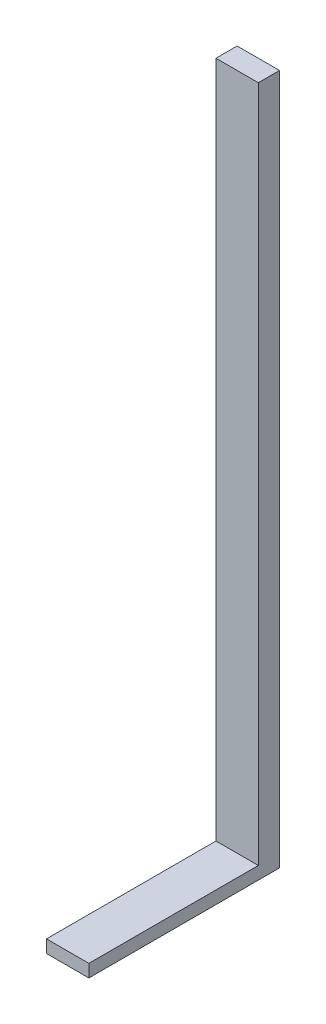
SolidWorks part; units mm, degrees
ref_plane "Front Plane" through (0, 0, 0) normal (0, 0, 1) x (1, 0, 0)
ref_plane "Top Plane" through (0, 0, 0) normal (0, 1, 0) x (1, 0, 0)
ref_plane "Right Plane" through (0, 0, 0) normal (1, 0, 0) x (0, 0, -1)
sketch "Sketch1" plane through (0, 0, 0) normal (1, 0, 0) x (0, 0, -1)
  line L0 (0, 0) -> (-45, 0)
  line L1 (-45, 0) -> (-45, 3)
  line L2 (-45, 3) -> (-5, 3)
  line L3 (-5, 3) -> (-5, 163)
  line L4 (-5, 163) -> (0, 163)
  line L5 (0, 163) -> (0, 0)
  dimension "D1" = 3
  dimension "D2" = 45
  dimension "D3" = 5
  dimension "D4" = 163
extrude "Boss-Extrude1" add sketch "Sketch1" along normal blind 10
